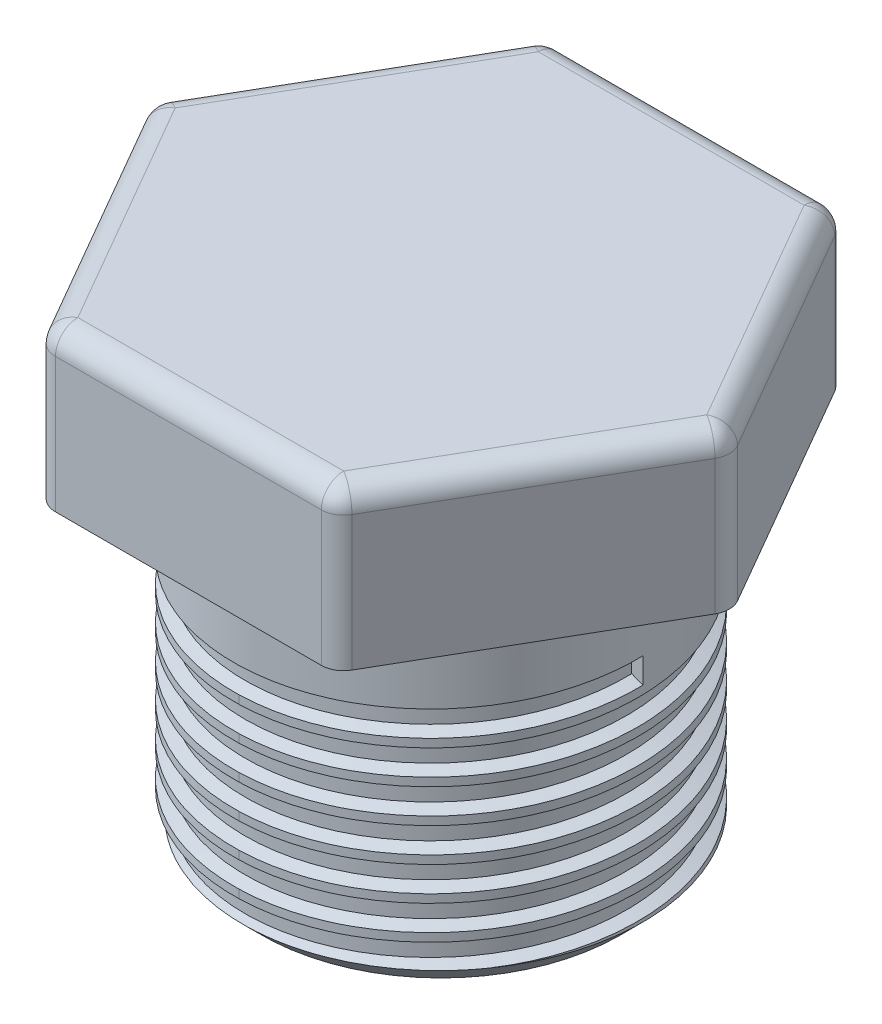
SolidWorks part; units mm, degrees
ref_plane "前视基准面" through (0, 0, 0) normal (0, 0, 1) x (1, 0, 0)
ref_plane "上视基准面" through (0, 0, 0) normal (0, 1, 0) x (1, 0, 0)
ref_plane "右视基准面" through (0, 0, 0) normal (1, 0, 0) x (0, 0, -1)
sketch "草图1" plane through (0, 0, 0) normal (0, 1, 0) x (1, 0, 0)
  line L1 (-13, 0) -> (-6.5, -11.2583)
  line L2 (-6.5, -11.2583) -> (6.5, -11.2583)
  line L3 (6.5, -11.2583) -> (13, 0)
  line L4 (13, 0) -> (6.5, 11.2583)
  line L5 (6.5, 11.2583) -> (-6.5, 11.2583)
  line L6 (-6.5, 11.2583) -> (-13, 0)
  circle A1 centre (0, 0) radius 11.2583 construction
extrude "凸台-拉伸1" add sketch "草图1" along normal blind 7
sketch "草图2" plane through (0, 0, 0) normal (0, -1, 0) x (1, 0, 0)
  circle A0 centre (0, 0) radius 9
extrude "凸台-拉伸2" add sketch "草图2" along normal blind 15
chamfer "倒角2" distance 1 angle 45 1 edges at (0, -15, -9)
fillet "圆角5" radius 1 1 edges at (6.5, 3.5, 11.2583)
fillet "圆角6" radius 1 1 edges at (13, 3.5, 0)
fillet "圆角7" radius 1 1 edges at (6.5, 3.5, -11.2583)
fillet "圆角8" radius 1 1 edges at (-6.5, 3.5, -11.2583)
fillet "圆角9" radius 1 1 edges at (-13, 3.5, 0)
fillet "圆角10" radius 1 1 edges at (-6.5, 3.5, 11.2583)
sketch "草图9" plane through (0, -15, 0) normal (0, -1, 0) x (1, 0, 0)
  circle A0 centre (0, 0) radius 9
curve "螺旋线/涡状线2" pitch 1.5 height 10.5 turns 7
sketch "草图10" plane through (0, 0, 0) normal (0, 0, 1) x (1, 0, 0)
  line L0 (8.5, -15.1636) -> (8.5, -14.5136)
  line L1 (9.1777, -15.419) -> (9.1777, -14.119)
  line L2 (8.5, -14.8386) -> (9.4331, -14.8386) construction
  line L3 (8.5, -14.5136) -> (9.1777, -14.119)
  line L4 (9.1777, -14.119) -> (9.2912, -14.1139)
  line L5 (9.1777, -15.419) -> (8.5, -15.1636)
sweep "切除-扫描1" cut profiles "草图10" path "螺旋线/涡状线2"
fillet "圆角13" radius 1 12 edges at (9.75, 7, 5.6292) (6.4226, 7, 11.1244) (9.75, 7, -5.6292) (12.8453, 7, 0) (0, 7, -11.2583) (6.4226, 7, -11.1244) (-9.75, 7, -5.6292) (-6.4226, 7, -11.1244) (-9.75, 7, 5.6292) (-12.8453, 7, 0) (0, 7, 11.2583) (-6.4226, 7, 11.1244)
